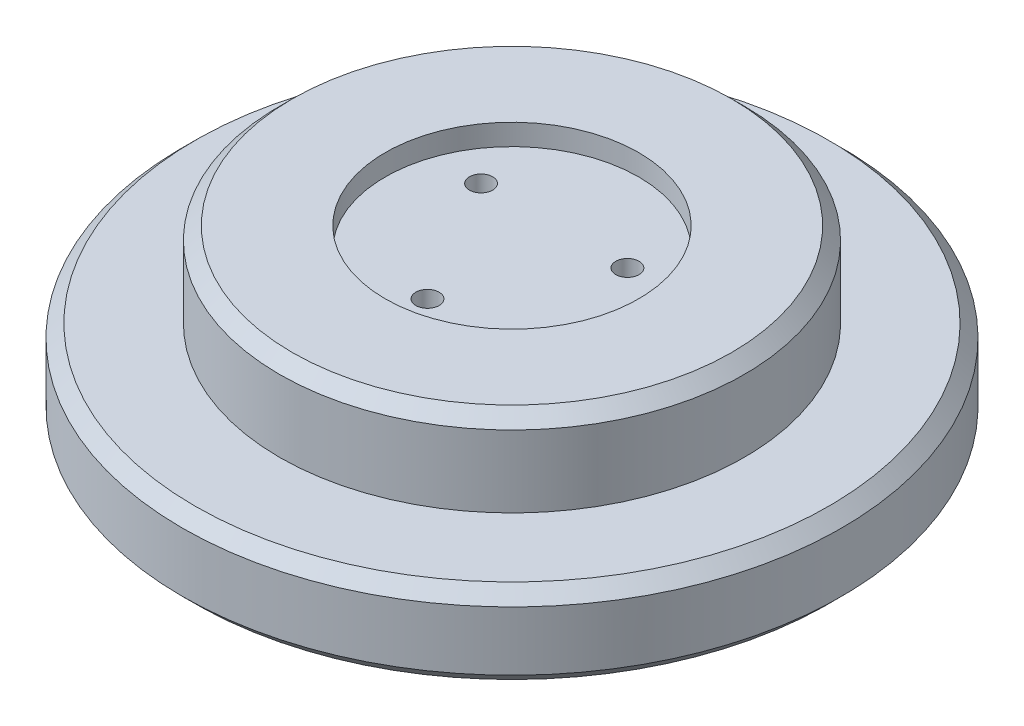
SolidWorks part; units mm, degrees
material "Gray Cast Iron"
ref_plane "Front Plane" through (0, 0, 0) normal (0, 0, 1) x (1, 0, 0)
ref_plane "Top Plane" through (0, 0, 0) normal (0, 1, 0) x (1, 0, 0)
ref_plane "Right Plane" through (0, 0, 0) normal (1, 0, 0) x (0, 0, -1)
sketch "Sketch1" plane through (0, 0, 0) normal (1, 0, 0) x (0, 0, -1)
  line L0 (0, 226.1544) -> (0, -214.3891) construction
  line L1 (0, 0) -> (-78, 0)
  line L2 (-78, 0) -> (-78, 20)
  line L3 (-78, 20) -> (-55, 20)
  line L4 (-55, 20) -> (-55, 40)
  line L5 (-55, 40) -> (-30, 40)
  line L6 (-30, 40) -> (-30, 35)
  line L7 (-30, 35) -> (0, 35)
  line L8 (0, 0) -> (0, 35)
  dimension "D1" = 78
  dimension "D2" = 55
  dimension "D3" = 30
  dimension "D4" = 20
  dimension "D5" = 40
  dimension "D6" = 5
revolve "Revolve1" add sketch "Sketch1" angle 360 about L0
sketch "Sketch2" plane through (0, 0, 0) normal (0, -1, 0) x (1, 0, 0)
  circle A0 centre (0, 0) radius 20
  circle A1 centre (0, 20) radius 5.5
  dimension "D1" = 40
  dimension "D2" = 11
hole_wizard "M6x0.5 Tapped Hole1" positions "3DSketch3" profile "Sketch6" tap size "M6x0.5" standard "DIN" end condition through all
sketch3d "3DSketch3"
  point P0 (0, 0, 20)
sketch "Sketch6" plane through (0, 0, 20) normal (1, 0, 0) x (0, 0, -1)
  line L0 (0, 0) -> (0, 40)
  line L1 (0, 40) -> (2.75, 40)
  line L2 (2.75, 40) -> (2.75, 0)
  line L5 (2.75, 0) -> (0, 0)
  line L11 (0, -6.35) -> (0, 107.95) construction
  dimension "Thru Tap Drill Dia." = 5.5
  dimension "Thru Tap Drill Depth" = 40
cosmetic thread "Hole Thread3" parameters "D2"=6
pattern_circular "CirPattern1" count 3 over 360 about axis through (0, 0, 0) along (0, 1, 0) of "M6x0.5 Tapped Hole1"
cosmetic thread "Hole Thread4" parameters "D2"=6
cosmetic thread "Hole Thread5" parameters "D2"=6
chamfer "Chamfer1" distance 3 angle 45 3 edges at (0, 0, 78) (0, 20, 78) (0, 40, 55)
sketch "Sketch7" plane through (0, 0, 0) normal (0, -1, 0) x (1, 0, 0)
  circle A0 centre (0, 20) radius 5
  circle A1 centre (17.3205, -10) radius 5
  circle A2 centre (-17.3205, -10) radius 5
  point P9 (0, 0)
  dimension "D1" = 10
  dimension "D2" = 3
extrude "Cut-Extrude1" cut sketch "Sketch7" against normal blind 5
